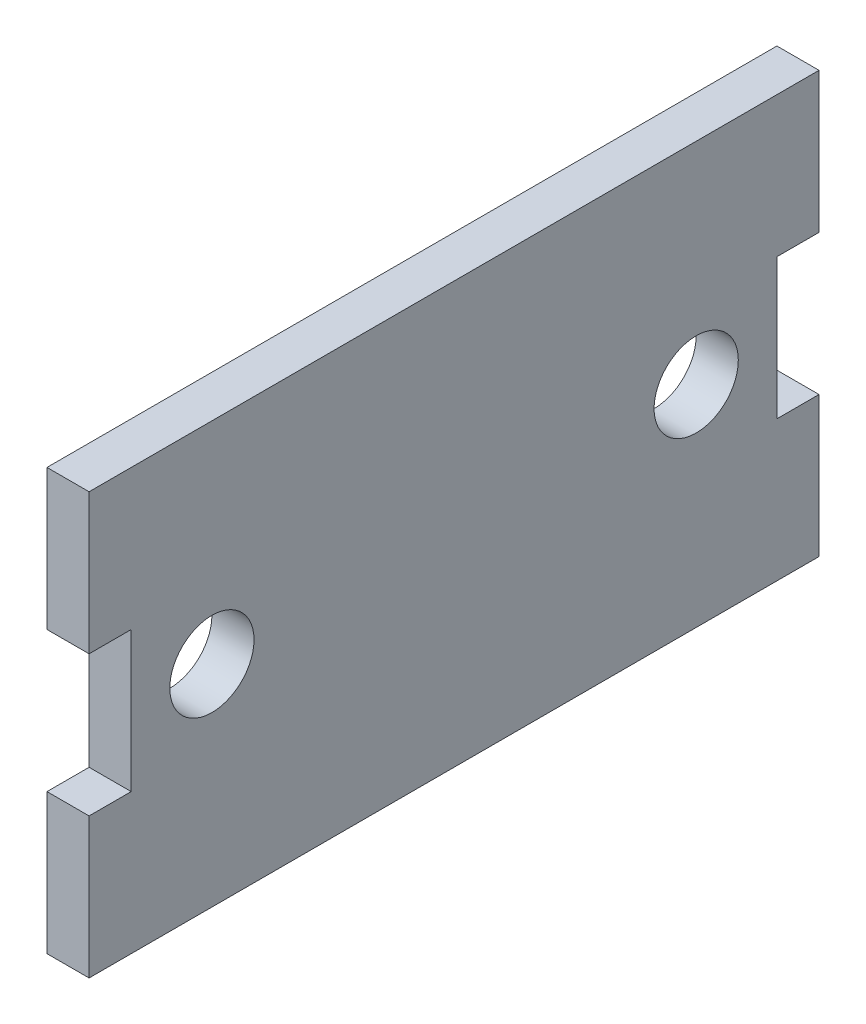
SolidWorks part; units mm, degrees
ref_plane "Front Plane" through (0, 0, 0) normal (1, 0, 0) x (0, 1, 0)
ref_plane "Top Plane" through (0, 0, 0) normal (0, 0, 1) x (0, 1, 0)
ref_plane "Right Plane" through (0, 0, 0) normal (0, 1, 0) x (-1, 0, 0)
sketch "Sketch1" plane through (0, 0, 0) normal (1, 0, 0) x (0, 1, 0)
  line L0 (0, 0) -> (0, 26)
  line L1 (0, 26) -> (5, 26)
  line L2 (5, 26) -> (5, 24.5)
  line L3 (5, 24.5) -> (10, 24.5)
  line L4 (10, 24.5) -> (10, 26)
  line L5 (10, 26) -> (15, 26)
  line L6 (15, 26) -> (15, 0)
  line L7 (15, 0) -> (10, 0)
  line L8 (10, 0) -> (10, 1.5)
  line L9 (10, 1.5) -> (5, 1.5)
  line L10 (5, 1.5) -> (5, 0)
  line L11 (5, 0) -> (0, 0)
  dimension "D1" = 26
  dimension "D2" = 15
  dimension "D3" = 5
  dimension "D4" = 1.5
extrude "Boss-Extrude1" add sketch "Sketch1" along normal blind 1.5
sketch "Sketch2" plane through (1.5, 0, 0) normal (1, 0, 0) x (0, 1, 0)
  line L0 (5, 1.5) -> (10, 1.5) construction
  line L1 (5, 1.5) -> (10, 1.5) construction
  line L2 (7.5, 4.375) -> (7.5, 1.5) construction
  line L5 (7.5, 21.625) -> (7.5, 24.5) construction
  line L6 (10, 24.5) -> (5, 24.5) construction
  circle A0 centre (7.5, 21.625) radius 1.5
  circle A1 centre (7.5, 4.375) radius 1.5
  point P7 (7.5, 1.5)
  dimension "D2" = 3
  dimension "D3" = 3
  dimension "D1" = 17.25
extrude "Cut-Extrude1" cut sketch "Sketch2" against normal through all
